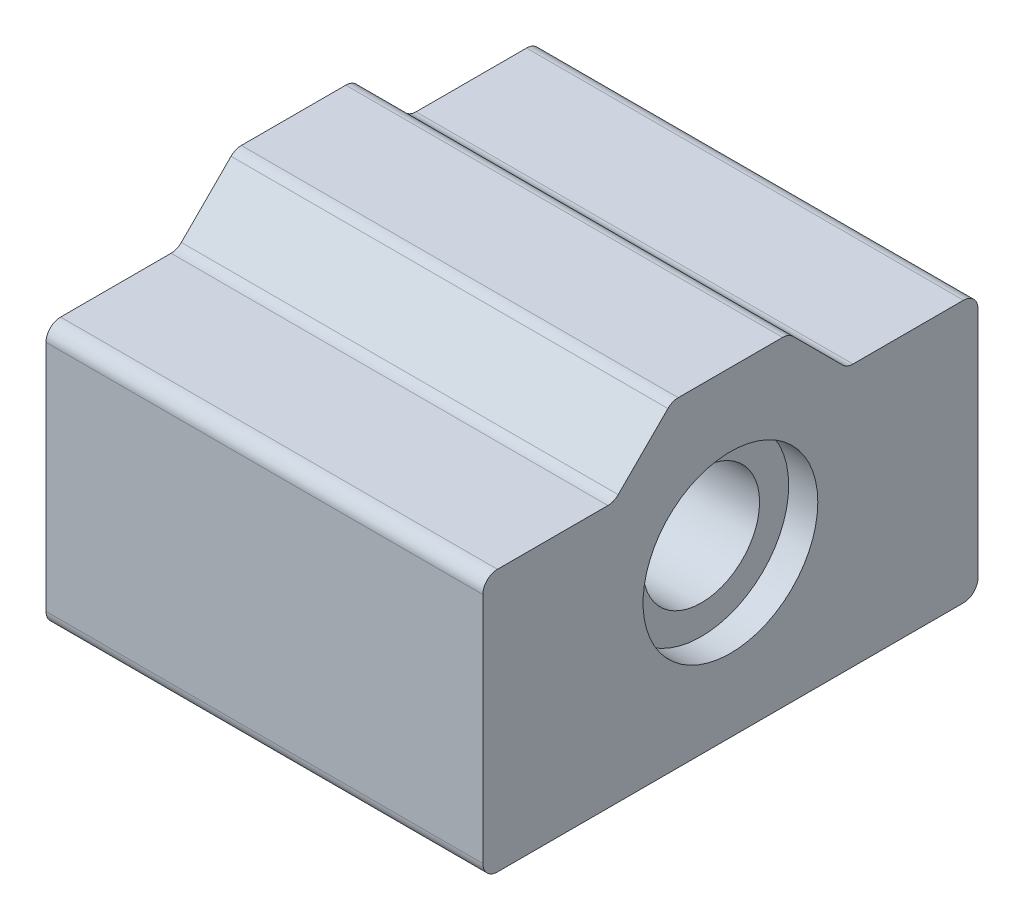
SolidWorks part; units mm, degrees
ref_plane "前视基准面" through (0, 0, 0) normal (0, 0, 1) x (1, 0, 0)
ref_plane "上视基准面" through (0, 0, 0) normal (0, 1, 0) x (1, 0, 0)
ref_plane "右视基准面" through (0, 0, 0) normal (1, 0, 0) x (0, 0, -1)
sketch "草图1" plane through (0, 0, 0) normal (1, 0, 0) x (0, 0, -1)
  line L0 (-12.1172, -1) -> (-12.1172, -17)
  line L1 (-11.1172, -18) -> (20.8828, -18)
  line L2 (21.8828, -17) -> (21.8828, -1)
  line L3 (20.8828, 0) -> (13.297, 0)
  line L4 (12.5899, 0.2929) -> (9.1757, 3.7071)
  line L5 (8.4686, 4) -> (1.297, 4)
  line L6 (0.5899, 3.7071) -> (-2.8243, 0.2929)
  line L7 (-3.5314, 0) -> (-11.1172, 0)
  circle A0 centre (4.8828, -7) radius 4
  arc A1 (-11.1172, -18) -> (-12.1172, -17) centre (-11.1172, -17) cw
  arc A2 (21.8828, -17) -> (20.8828, -18) centre (20.8828, -17) cw
  arc A3 (-2.8243, 0.2929) -> (-3.5314, 0) centre (-3.5314, 1) cw
  arc A4 (-12.1172, -1) -> (-11.1172, 0) centre (-11.1172, -1) cw
  arc A5 (1.297, 4) -> (0.5899, 3.7071) centre (1.297, 3) ccw
  arc A6 (9.1757, 3.7071) -> (8.4686, 4) centre (8.4686, 3) ccw
  arc A7 (13.297, 0) -> (12.5899, 0.2929) centre (13.297, 1) cw
  arc A8 (21.8828, -1) -> (20.8828, 0) centre (20.8828, -1) ccw
  point P13 (-12.1172, -18)
  point P16 (21.8828, -18)
  point P19 (-3.1172, 0)
  point P22 (-12.1172, 0)
  point P25 (0.8828, 4)
  point P28 (8.8828, 4)
  point P31 (12.8828, 0)
  point P34 (21.8828, 0)
  dimension "D9" = 8
  dimension "D10" = 17
  dimension "D13" = 1
  dimension "D1" = 34
  dimension "D2" = 18
  dimension "D3" = 22
  dimension "D4" = 9
  dimension "D5" = 18
  dimension "D6" = 9
  dimension "D7" = 4
  dimension "D8" = 4
  dimension "D11" = 11
  dimension "D12" = 11
extrude "凸台-拉伸1" add sketch "草图1" along normal blind 30
sketch "草图6" plane through (0, -18, 0) normal (0, -1, 0) x (1, 0, 0)
  line L0 (30, -4.8828) -> (0, -4.8828) construction
  line L1 (0, 11.1172) -> (0, -20.8828) construction
  line L2 (0, -0.8828) -> (0, -8.8828) construction
  circle A0 centre (24, -16.8828) radius 2
  circle A1 centre (6, -16.8828) radius 2
  circle A2 centre (6, 7.1172) radius 2
  circle A3 centre (24, 7.1172) radius 2
  point P12 (0, -4.8828)
  dimension "D1" = 4
  dimension "D2" = 4
  dimension "D3" = 4
  dimension "D4" = 4
  dimension "D5" = 18
  dimension "D6" = 18
  dimension "D7" = 24
  dimension "D8" = 24
  dimension "D9" = 12
  dimension "D10" = 12
  dimension "D11" = 12
  dimension "D12" = 12
  dimension "D13" = 6
extrude "切除-拉伸5" cut sketch "草图6" against normal blind 8
sketch "草图7" plane through (0, 0, 0) normal (-1, 0, 0) x (0, 0, 1)
  circle A2 centre (-4.8828, -7) radius 6
  circle A3 centre (-4.8828, -7) radius 6
  dimension "D1" = 2
extrude "切除-拉伸6" cut sketch "草图7" against normal blind 2
sketch "草图8" plane through (30, 0, 0) normal (1, 0, 0) x (0, 0, -1)
  circle A2 centre (4.8828, -7) radius 6
  circle A3 centre (4.8828, -7) radius 6
  dimension "D1" = 2
extrude "切除-拉伸7" cut sketch "草图8" against normal blind 2
